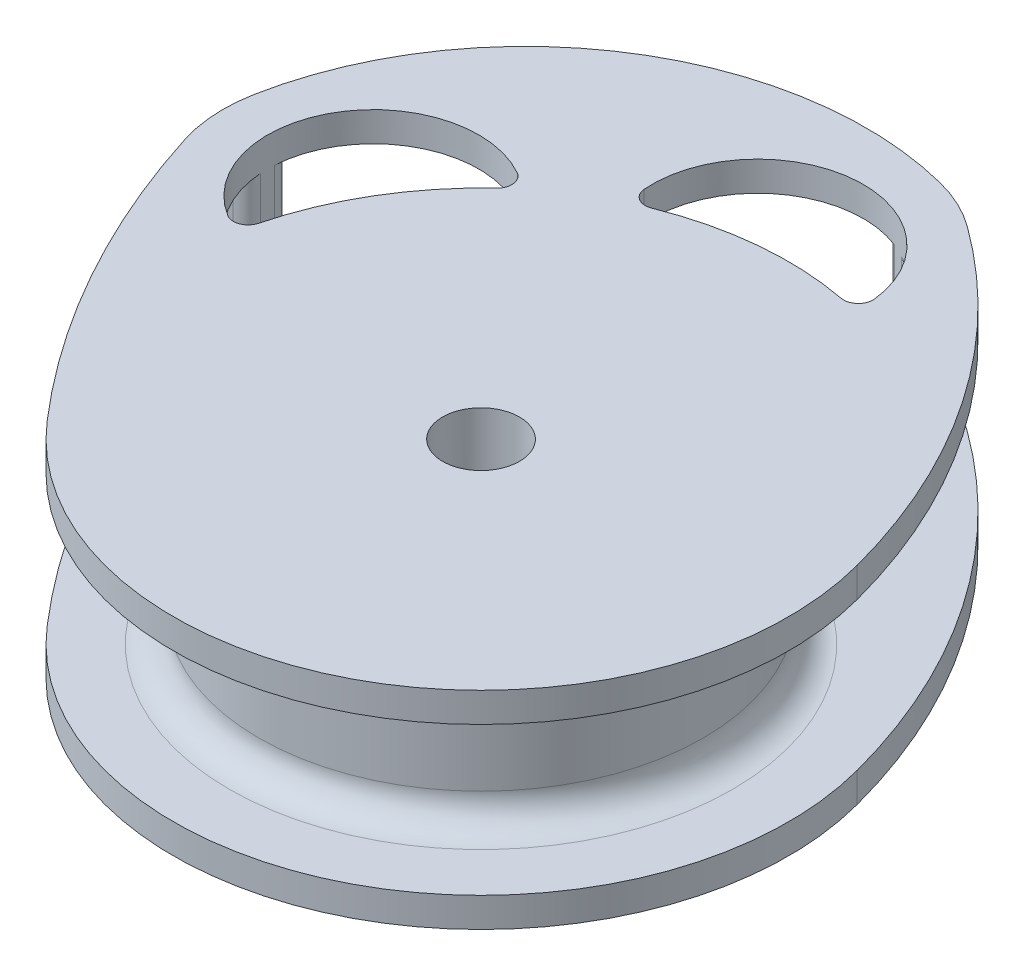
SolidWorks part; units mm, degrees
ref_plane "Front Plane" through (0, 0, 0) normal (0, 0, 1) x (1, 0, 0)
ref_plane "Top Plane" through (0, 0, 0) normal (0, 1, 0) x (1, 0, 0)
ref_plane "Right Plane" through (0, 0, 0) normal (1, 0, 0) x (0, 0, -1)
sketch "Sketch1" plane through (0, 0, 0) normal (0, 1, 0) x (1, 0, 0)
  arc A0 (-19.9613, -17.2791) -> (25.5175, 6.7735) centre (0, 0) ccw
  arc A1 (5.0514, 36.6837) -> (0.6543, 38.7551) centre (-2.5364, 26.2791) ccw
  arc A3 (-35.3615, 15.8728) -> (-34.9875, 9.5698) centre (-22.7118, 13.4609) ccw
  arc A4 (-16.8178, 20.3515) -> (-25.9268, 4.9824) centre (-22.7118, 13.4609) ccw
  arc A5 (-16.8178, 20.3515) -> (-25.9268, 4.9824) centre (0, 0) ccw
  arc A8 (0.6543, 38.7551) -> (-35.3615, 15.8728) centre (-6.6004, 10.3888) ccw
  circle A9 centre (0, 0) radius 26.4012 construction
  arc A12 (6.5047, 25.5873) -> (-11.2784, 23.8709) centre (0, 0) ccw
  arc A13 (6.5047, 25.5873) -> (-11.2784, 23.8709) centre (-2.5364, 26.2791) ccw
  arc A14 (-34.9875, 9.5698) -> (-19.9613, -17.2791) centre (37.6557, 32.5958) ccw
  arc A15 (5.0514, 36.6837) -> (25.5175, 6.7735) centre (-26.9105, -7.1433) cw
  point P16 (0, 0)
  point P18 (0, 0)
  point P19 (0, 0)
  dimension "D1" = 2
  dimension "D2" = 3.81
  dimension "D3" = 3.81
extrude "Boss-Extrude1" add sketch "Sketch1" along normal blind 8.89 and the other way blind 8.89
sketch "Sketch2" plane through (0, 0, 0) normal (0, 1, 0) x (1, 0, 0)
  circle A0 centre (0, 0) radius 19.05
  dimension "D1" = 38.1
extrude "Cut-Extrude1" cut sketch "Sketch2" against normal blind 6.35 and the other way blind 6.35 flip side to cut
fillet "Fillet2" radius 2.54 1 edges at (0, -6.35, 19.05)
fillet "Fillet3" radius 2.54 1 edges at (0, 6.35, 19.05)
sketch "Sketch3" plane through (0, -8.89, 0) normal (0, -1, 0) x (1, 0, 0)
  circle A0 centre (0, 0) radius 3.302
  dimension "D1" = 6.604
extrude "Cut-Extrude2" cut sketch "Sketch3" against normal through all both and the other way through all
fillet "Fillet7" radius 1.27 8 edges at (-25.9268, -7.62, -4.9824) (-16.8178, -7.62, -20.3515) (-25.9268, 7.62, -4.9824) (-16.8178, 7.62, -20.3515) (6.5047, -7.62, -25.5873) (-11.2784, -7.62, -23.8709) (6.5047, 7.62, -25.5873) (-11.2784, 7.62, -23.8709)
sketch "Sketch4" plane through (0, -6.35, 0) normal (0, 1, 0) x (1, 0, 0)
  line L0 (-22.3017, 35.1021) -> (-6.6004, 10.3888) construction
  arc A0 (0.6543, 38.7551) -> (-35.3615, 15.8728) centre (-6.6004, 10.3888) ccw construction
  circle A1 centre (-19.5458, 30.7645) radius 2.7998
extrude "Boss-Extrude2" add sketch "Sketch4" along normal blind 12.7
fillet "Fillet8" radius 1.27 1 edges at (-19.5458, 6.35, -27.9646)
fillet "Fillet9" radius 1.27 1 edges at (-19.5458, -6.35, -27.9646)
sketch "Sketch5" plane through (0, -6.35, 0) normal (0, 1, 0) x (1, 0, 0)
  line L0 (5.0514, 36.6837) -> (2.8064, 33.6054)
  line L1 (0.6543, 38.7551) -> (-0.2897, 35.0639)
  line L2 (-22.3017, 35.1021) -> (0, 0) construction
  line L3 (-35.3545, 11.0123) -> (-31.614, 11.7368)
  line L4 (-35.3615, 15.8728) -> (-31.6189, 15.1592)
  arc A0 (6.4709, 27.3226) -> (-11.5771, 25.5806) centre (-2.5364, 26.2791) ccw construction
  arc A1 (5.0514, 36.6837) -> (0.6543, 38.7551) centre (-2.5364, 26.2791) ccw construction
  arc A2 (2.8064, 33.6054) -> (-0.2897, 35.0639) centre (-2.5364, 26.2791) ccw
  arc A3 (5.0514, 36.6837) -> (0.6543, 38.7551) centre (-2.5364, 26.2791) ccw
  arc A5 (0.6543, 38.7551) -> (-35.3615, 15.8728) centre (-6.6004, 10.3888) ccw construction
  arc A6 (-35.3545, 11.0123) -> (-35.3615, 15.8728) centre (-22.7118, 13.4609) cw
  arc A7 (-31.614, 11.7368) -> (-31.6189, 15.1592) centre (-22.7118, 13.4609) cw
  point P9 (-22.3017, 35.1021)
  point P13 (-6.6004, 10.3888)
  point P14 (0, 0)
extrude "Boss-Extrude3" add sketch "Sketch5" along normal blind 12.7
fillet "Fillet10" radius 1.27 4 edges at (0.6543, 0, -38.7551) (-0.2897, 0, -35.0639) (2.8064, 0, -33.6054) (5.0514, 0, -36.6837)
fillet "Fillet11" radius 1.27 4 edges at (-31.6189, 0, -15.1592) (-35.3615, 0, -15.8728) (-35.3545, 0, -11.0123) (-31.614, 0, -11.7368)
